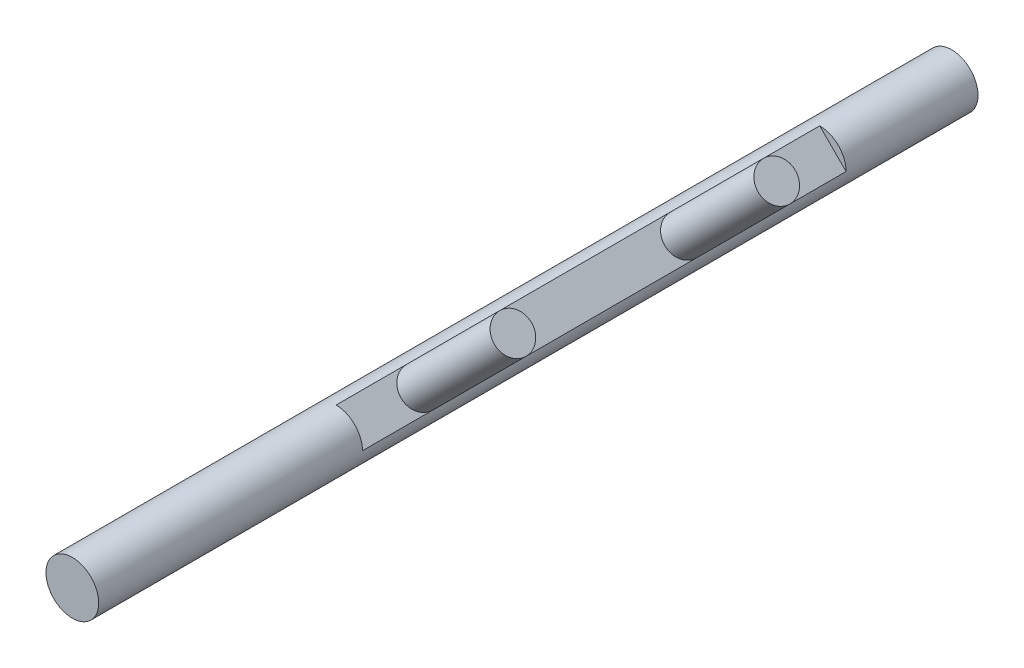
SolidWorks part; units mm, degrees
ref_plane "Plan de face" through (0, 0, 0) normal (0, 0, 1) x (1, 0, 0)
ref_plane "Plan de dessus" through (0, 0, 0) normal (0, 1, 0) x (1, 0, 0)
ref_plane "Plan de droite" through (0, 0, 0) normal (1, 0, 0) x (0, 0, -1)
sketch "Esquisse1" plane through (0, 0, 0) normal (0, 0, 1) x (1, 0, 0)
  circle A0 centre (0, 0) radius 3
extrude "Boss.-Extru.1" add sketch "Esquisse1" along normal blind 15
sketch "Esquisse2" plane through (0, 0, 0) normal (0, 0, -1) x (-1, 0, 0)
  circle A0 centre (0, 0) radius 2.5
extrude "Enlèv. mat.-Extru.1" cut sketch "Esquisse2" against normal blind 5
sketch "Esquisse3" plane through (0, 0, 15) normal (0, 0, 1) x (1, 0, 0)
  line L0 (0, 3) -> (3, 0)
  arc A0 (0, 3) -> (3, 0) centre (0, 0) ccw
  circle A1 centre (0, 0) radius 3 construction
extrude "Boss.-Extru.2" add sketch "Esquisse3" along normal blind 55
sketch "Esquisse4" plane through (1.5, 1.5, 0) normal (0.7071, 0.7071, 0) x (0, 0, -1)
  line L0 (-70, -2.1213) -> (-70, 2.1213) construction
  circle A0 centre (-62, 0) radius 2.1213
  circle A1 centre (-32, 0) radius 2.1213
  dimension "D1" = 8
  dimension "D2" = 38
ref_plane "Plan1" through (1.5, 1.5, 0) normal (0.7071, 0.7071, 0) x (0.7071, -0.7071, 0)
extrude "Boss.-Extru.3" add sketch "Esquisse4" along normal blind 15 contours A1 | A0
sketch "Esquisse5" plane through (0, 0, 70) normal (0, 0, 1) x (1, 0, 0)
  circle A0 centre (0, 0) radius 3
extrude "Boss.-Extru.4" add sketch "Esquisse5" along normal blind 30
